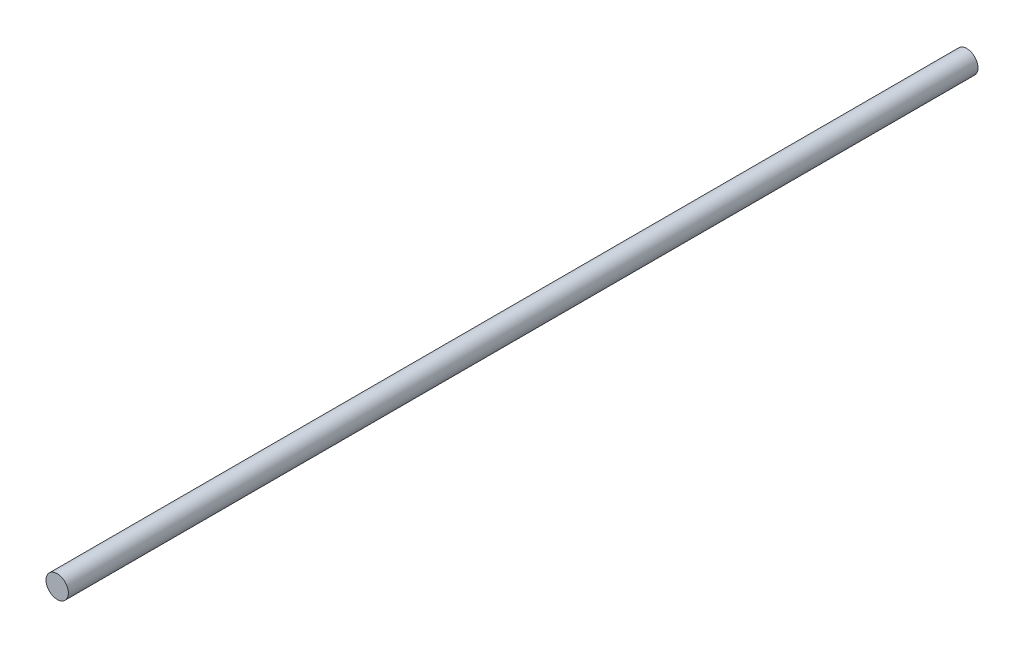
SolidWorks part; units mm, degrees
material "6061-T4 (SS)"
ref_plane "Front Plane" through (0, 0, 0) normal (0, 0, 1) x (1, 0, 0)
ref_plane "Top Plane" through (0, 0, 0) normal (0, 1, 0) x (1, 0, 0)
ref_plane "Right Plane" through (0, 0, 0) normal (1, 0, 0) x (0, 0, -1)
sketch "Sketch1" plane through (0, 0, 0) normal (0, 0, 1) x (1, 0, 0)
  circle A0 centre (0, 0) radius 3.175
  dimension "D1" = 6.35
extrude "Boss-Extrude1" add sketch "Sketch1" along normal blind 258.0917
equation "\"Deflection\"= 0.009"
equation "\"Force\"= 400"
equation "\"Yield\"= 40000"
equation "\"Elastic\"= 9200000"
equation "\"Diameter\"= 0.25"
equation "\"Area\"= ( pi / 4 ) * ( \"Diameter\" ) ^ 2"
equation "\"Length\"= \"Deflection\" * \"Area\" * \"Elastic\" / \"Force\""
equation "\"D1@Sketch1\"=\"Diameter\""
equation "\"D1@Boss-Extrude1\"=\"Length\""
